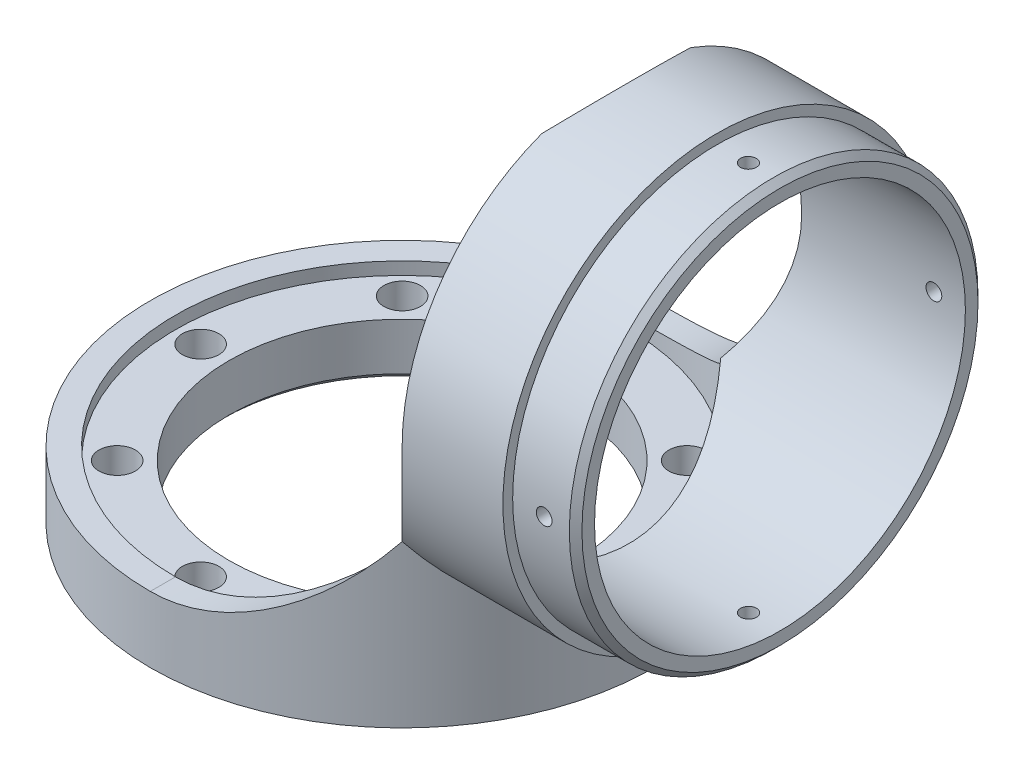
SolidWorks part; units mm, degrees
ref_plane "前视基准面" through (0, 0, 0) normal (0, 0, 1) x (1, 0, 0)
ref_plane "上视基准面" through (0, 0, 0) normal (0, 1, 0) x (1, 0, 0)
ref_plane "右视基准面" through (0, 0, 0) normal (1, 0, 0) x (0, 0, -1)
sketch "草图1" plane through (0, 0, 0) normal (0, 1, 0) x (1, 0, 0)
  circle A0 centre (0, 0) radius 40
  circle A1 centre (0, 0) radius 27.5
  dimension "D1" = 80
  dimension "D2" = 55
extrude "凸台-拉伸1" add sketch "草图1" along normal blind 80.5
ref_plane "基准面1" through (60, 0, 0) normal (1, 0, 0) x (0, 0, -1)
sketch "草图3" plane through (60, 0, 0) normal (1, 0, 0) x (0, 0, -1)
  circle A0 centre (0, 44.5) radius 34
  dimension "D1" = 68
  dimension "D2" = 44.5
extrude "凸台-拉伸3" add sketch "草图3" against normal up to surface (38.9287 mm away)
sketch "草图20" plane through (0, 80.5, 0) normal (0, 1, 0) x (1, 0, 0)
  circle A0 centre (0, 0) radius 32 construction
  circle A1 centre (32, 0) radius 2.9
  dimension "D1" = 64
  dimension "D2" = 5.8
extrude "切除-拉伸4" cut sketch "草图20" against normal offset from surface (76.5 mm away) 4 up to face at (0, 0, 40)
sketch "草图23" plane through (0, 4, 0) normal (0, 1, 0) x (1, 0, 0)
  circle A0 centre (32, 0) radius 1.6
  dimension "D1" = 3.2
extrude "切除-拉伸5" cut sketch "草图23" against normal up to next
pattern_circular "阵列(圆周)5" count 8 over 360 about axis through (0, 0, 0) along (0, 1, 0) of "切除-拉伸4", "切除-拉伸5"
sketch "草图16" plane through (0, 0, 0) normal (0, 0, 1) x (1, 0, 0)
  line L0 (0, 2.4377) -> (0, 78.5) construction
  line L2 (60, 10.5) -> (60, 78.5) construction
  line L3 (60, 44.5) -> (-103.3904, 44.5) construction
  line L4 (60, 10.5) -> (60, 78.5) construction
  line L6 (0, 10.5) -> (-103.3904, 10.5)
  line L8 (0, 78.5) -> (-103.3904, 78.5)
  line L9 (-103.3904, 10.5) -> (-103.3904, 78.5)
  arc A0 (0, 10.5) -> (0, 78.5) centre (0, 44.5) ccw
  dimension "D1" = 68
extrude "切除-拉伸1" cut sketch "草图16" against normal through all both and the other way through all
sketch "草图30" plane through (60, 0, 0) normal (1, 0, 0) x (0, 0, -1)
  point P0 (0, 44.5)
ref_plane "基准面4" through (0, 44.5, 0) normal (0, 1, 0) x (1, 0, 0)
sketch "草图17" plane through (0, 80.5, 0) normal (0, 1, 0) x (1, 0, 0)
  line L1 (-63.6128, 40) -> (34, 40)
  line L2 (-63.6128, 40) -> (-63.6128, -40)
  line L3 (-63.6128, -40) -> (34, -40)
  line L4 (34, 40) -> (34, -40)
  line L5 (-63.6128, 40) -> (34, -40) construction
  line L6 (-63.6128, -40) -> (34, 40) construction
  circle A2 centre (0, 0) radius 40 construction
  point P0 (-14.8064, 0)
  dimension "D1" = 34
extrude "切除-拉伸2" cut sketch "草图17" against normal up to surface (36 mm away) up to plane "基准面4"
sketch "草图18" plane through (60, 0, 0) normal (1, 0, 0) x (0, 0, -1)
  circle A0 centre (0, 44.5) radius 34 construction
  circle A2 centre (0, 44.5) radius 32.45
  circle A5 centre (0, 44.5) radius 34
  dimension "D1" = 64.9
extrude "切除-拉伸3" cut sketch "草图18" against normal blind 10
sketch "草图24" plane through (0, 80.5, 0) normal (0, 1, 0) x (1, 0, 0)
  circle A0 centre (0, 0) radius 36
  dimension "D1" = 72
extrude "切除-拉伸6" cut sketch "草图24" against normal offset from surface (72 mm away) 2 up to face at (-29.1, 10.5, 0) offset beyond the face yes
sketch "草图26" plane through (60, 0, 0) normal (1, 0, 0) x (0, 0, -1)
  circle A0 centre (0, 44.5) radius 29.45
  circle A1 centre (0, 44.5) radius 32.45 construction
  dimension "D1" = 3
extrude "切除-拉伸7" cut sketch "草图26" against normal up to next
ref_plane "基准面2" through (0, 76.95, 0) normal (0, 1, 0) x (1, 0, 0)
sketch "草图27" plane through (0, 76.95, 0) normal (0, 1, 0) x (1, 0, 0)
  line L0 (50, 0) -> (55, 0)
  line L1 (50, -32.45) -> (50, 32.45) construction
  dimension "D1" = 5
hole_wizard "M3 螺纹孔1" positions "草图28" profile "草图29" tap size "M3" standard "GB"
sketch "草图28" plane through (0, 76.95, 0) normal (0, 1, 0) x (1, 0, 0)
  point P0 (55, 0)
sketch "草图29" plane through (55, 76.95, 0) normal (1, 0, 0) x (0, 0, 1)
  line L0 (0, 0) -> (0, 3)
  line L1 (0, 3) -> (1.25, 3)
  line L2 (1.25, 3) -> (1.25, 0)
  line L5 (1.25, 0) -> (0, 0)
  line L11 (0, -6.35) -> (0, 107.95) construction
  dimension "通孔螺纹孔钻头直径" = 2.5
  dimension "通孔螺纹孔钻头深度" = 3
cosmetic thread "孔螺蚊线1" parameters "D2"=3
pattern_circular "阵列(圆周)6" count 4 over 360 about axis through (50, 44.5, 0) along (1, 0, 0) of "M3 螺纹孔1"
cosmetic thread "孔螺蚊线2" parameters "D2"=3
cosmetic thread "孔螺蚊线3" parameters "D2"=3
cosmetic thread "孔螺蚊线4" parameters "D2"=3
sketch "草图31" plane through (50, 0, 0) normal (1, 0, 0) x (0, 0, -1)
  line L0 (21.0713, 71.1833) -> (21.0713, 80.5) construction
  line L1 (21.0713, 80.5) -> (-21.0713, 80.5) construction
  line L2 (-21.0713, 80.5) -> (-21.0713, 71.1833) construction
  line L3 (-21.0713, 80.5) -> (-21.0713, 71.1833)
  line L4 (21.0713, 80.5) -> (-21.0713, 80.5)
  line L5 (21.0713, 71.1833) -> (21.0713, 80.5)
  circle A2 centre (0, 44.5) radius 34 construction
  arc A3 (21.0713, 71.1833) -> (-21.0713, 71.1833) centre (0, 44.5) ccw
extrude "切除-拉伸8" cut sketch "草图31" against normal through all
ref_plane "基准面5" through (0, 10.5, 0) normal (0, -1, 0) x (-1, 0, 0)
sketch "草图32" plane through (0, 10.5, 0) normal (0, -1, 0) x (-1, 0, 0)
  line L0 (-45, 7.5) -> (-45, -7.5) construction
  line L5 (-41, 7.5) -> (-41, -7.5)
  line L6 (-49, 7.5) -> (-49, -7.5)
  arc A0 (-41, 7.5) -> (-49, 7.5) centre (-45, 7.5) ccw
  arc A1 (-49, -7.5) -> (-41, -7.5) centre (-45, -7.5) ccw
  point P2 (-45, 0)
  dimension "D1" = 15
  dimension "D2" = 8
  dimension "D3" = 45
extrude "切除-拉伸9" [suppressed] cut sketch "草图32" against normal up to next
chamfer "倒角1" distance 1 angle 45 1 edges at (60, 44.5, -32.45)
chamfer "倒角2" distance 1 angle 45 1 edges at (0, 0, 27.5)
equation "\"、\"=80.5"
